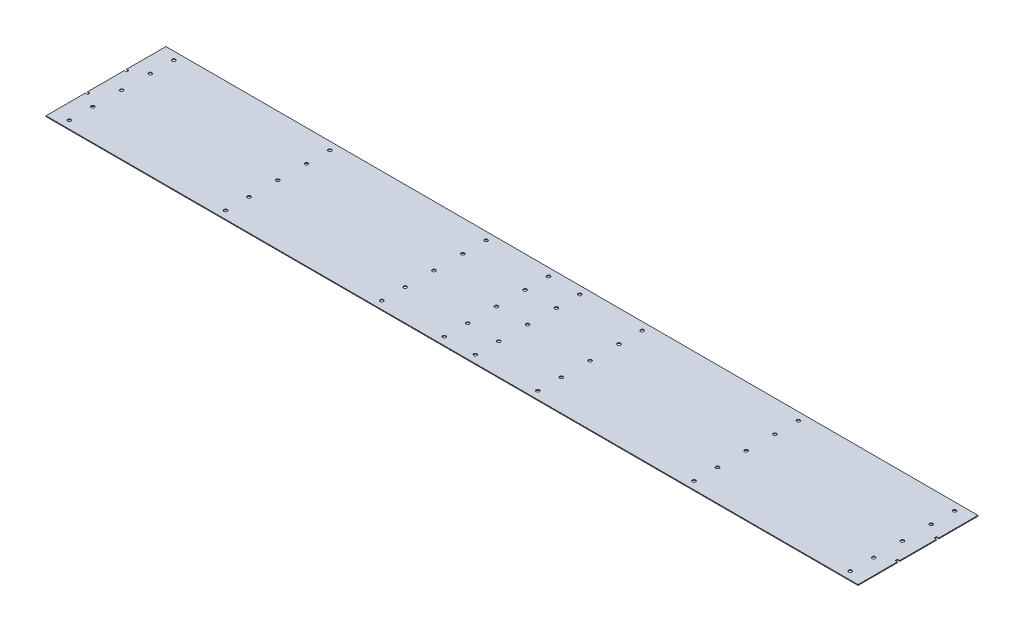
SolidWorks part; units mm, degrees
ref_plane "Front Plane" through (0, 0, 0) normal (0, 0, 1) x (1, 0, 0)
ref_plane "Top Plane" through (0, 0, 0) normal (0, 1, 0) x (1, 0, 0)
ref_plane "Right Plane" through (0, 0, 0) normal (1, 0, 0) x (0, 0, -1)
sketch "Sketch1" plane through (0, 0, 0) normal (0, 1, 0) x (1, 0, 0)
  line L0 (-20, -26.5) -> (-20, -76.8)
  line L1 (-20, -76.8) -> (1020, -76.8)
  line L2 (1020, -76.8) -> (1020, -26.5)
  line L3 (1020, -26.5) -> (-20, -26.5) construction
  line L4 (0, 0) -> (-17, 0) construction
  line L5 (-20, -26.5) -> (-17, -26.5)
  line L7 (-17, 26.5) -> (-20, 26.5)
  line L8 (-20, 26.5) -> (-20, 76.8)
  line L9 (-20, 76.8) -> (1020, 76.8)
  line L10 (1020, 76.8) -> (1020, 26.5)
  line L11 (1020, 26.5) -> (1017, 26.5)
  line L13 (1017, -26.5) -> (1020, -26.5)
  line L14 (0, 36.8) -> (480, 36.8) construction
  line L15 (-17, 26.5) -> (-17, 23.5)
  line L16 (-17, 26.5) -> (1017, 26.5) construction
  line L17 (1017, 26.5) -> (1017, -26.5) construction
  line L18 (-17, 26.5) -> (-17, -26.5) construction
  line L19 (-17, 23.5) -> (-20, 23.5)
  line L20 (-20, 23.5) -> (-20, -23.5)
  line L21 (-20, -23.5) -> (-17, -23.5)
  line L22 (-17, -23.5) -> (-17, -26.5)
  line L23 (1017, 26.5) -> (1017, 23.5)
  line L24 (1017, 23.5) -> (1020, 23.5)
  line L25 (1020, 23.5) -> (1020, -23.5)
  line L26 (1020, -23.5) -> (1017, -23.5)
  line L27 (1017, -23.5) -> (1017, -26.5)
  line L28 (1020, 0) -> (1017, 0) construction
  line L29 (480, 36.8) -> (480, -36.8) construction
  line L30 (-17, 0) -> (-20, 0) construction
  line L31 (0, 36.8) -> (0, -36.8) construction
  line L32 (480, -36.8) -> (0, -36.8) construction
  line L33 (0, 36.8) -> (0, 66.8) construction
  line L34 (0, 66.8) -> (480, 66.8) construction
  line L35 (480, 66.8) -> (480, 36.8) construction
  line L36 (480, -36.8) -> (480, -66.8) construction
  line L37 (480, -66.8) -> (0, -66.8) construction
  line L38 (0, -66.8) -> (0, -36.8) construction
  line L39 (0, 0) -> (480, 0) construction
  line L40 (200, 66.8) -> (200, 36.8) construction
  line L41 (200, 36.8) -> (200, 0) construction
  line L42 (200, 0) -> (200, -36.8) construction
  line L43 (200, -36.8) -> (200, -66.8) construction
  line L44 (500, 76.8) -> (500, -76.8) construction
  line L45 (480, 66.8) -> (500, 66.8) construction
  line L46 (500, 66.8) -> (520, 66.8) construction
  line L47 (520, 66.8) -> (520, -66.8) construction
  line L48 (520, -66.8) -> (480, -66.8) construction
  line L49 (480, -36.8) -> (520, -36.8) construction
  line L50 (400, 66.8) -> (400, -66.8) construction
  line L51 (480, 0) -> (520, 0) construction
  line L53 (480, 36.8) -> (520, 36.8) construction
  line L54 (600, 66.8) -> (600, -66.8) construction
  line L56 (800, 66.8) -> (800, -66.8) construction
  line L58 (1000, 66.8) -> (1000, -66.8) construction
  circle A0 centre (0, -36.8) radius 2.15
  circle A30 centre (0, 36.8) radius 2.15
  circle A31 centre (0, -66.8) radius 2.15
  circle A32 centre (0, 66.8) radius 2.15
  circle A33 centre (200, -66.8) radius 2.15
  circle A34 centre (200, -36.8) radius 2.15
  circle A35 centre (200, 36.8) radius 2.15
  circle A36 centre (200, 66.8) radius 2.15
  circle A53 centre (0, 0) radius 2.15
  circle A54 centre (480, 0) radius 2.15
  circle A55 centre (200, 0) radius 2.15
  circle A59 centre (480, 66.8) radius 2.15
  circle A60 centre (480, 36.8) radius 2.15
  circle A61 centre (480, -36.8) radius 2.15
  circle A62 centre (480, -66.8) radius 2.15
  circle A63 centre (400, -66.8) radius 2.15
  circle A64 centre (400, -36.8) radius 2.15
  circle A65 centre (400, 36.8) radius 2.15
  circle A66 centre (400, 66.8) radius 2.15
  circle A67 centre (600, -66.8) radius 2.15
  circle A68 centre (600, -36.8) radius 2.15
  circle A69 centre (600, 36.8) radius 2.15
  circle A70 centre (600, 66.8) radius 2.15
  circle A71 centre (800, -66.8) radius 2.15
  circle A72 centre (800, -36.8) radius 2.15
  circle A73 centre (800, 36.8) radius 2.15
  circle A74 centre (800, 66.8) radius 2.15
  circle A75 centre (1000, -66.8) radius 2.15
  circle A76 centre (1000, -36.8) radius 2.15
  circle A77 centre (1000, 36.8) radius 2.15
  circle A78 centre (1000, 66.8) radius 2.15
  circle A79 centre (520, -66.8) radius 2.15
  circle A80 centre (520, -36.8) radius 2.15
  circle A81 centre (520, 0) radius 2.15
  circle A82 centre (520, 36.8) radius 2.15
  circle A83 centre (520, 66.8) radius 2.15
  circle A84 centre (600, 0) radius 2.15
  circle A85 centre (800, 0) radius 2.15
  circle A86 centre (1000, 0) radius 2.15
  circle A87 centre (400, 0) radius 2.15
  point P2 (-18.5, 23.5)
  point P17 (0, 51.8)
  dimension "D12" = 4.3
  dimension "D8" = 3
  dimension "D1" = 3
  dimension "D6" = 30
  dimension "D7" = 10
  dimension "D4" = 20
  dimension "D15" = 200
  dimension "D3" = 13.3
  dimension "D11" = 13.3
  dimension "D2" = 47
  dimension "D5" = 20
  dimension "D10" = 40
  dimension "D9" = 6
  dimension "D14" = 2
extrude "Boss-Extrude1" add sketch "Sketch1" along normal blind 1 contours L27 L26 L25 L24 L23 L11 L10 L9 L8 L7 L15 L19 L20 L21 L22 L5 L0 L1 L2 L13 A54 A53 A36 A35 A34 A33 A32 A31 A30 A0
equation "\"skin_sheetmetal_thickness\"= 0.80"
equation "\"base_width_skin_spacer\" = \"base_width_skin_target_width\" - 4 * \"skin_sheetmetal_thickness\" - 2 * \"base_width_skin_target_bend_radius\""
equation "\"base_width_skin_inner\" = \"base_width_skin_spacer\" + 2 * \"skin_sheetmetal_thickness\""
equation "\"base_width_skin_outer\" = \"base_width_skin_inner\" + 2 * \"skin_sheetmetal_thickness\""
equation "\"bend_cut_width\"= 3"
equation "\"bend_cut_length\"= 3"
equation "\"bend_offset_inner\"= 12.5"
equation "\"bend_offset_outer\" = \"bend_offset_inner\" + \"skin_sheetmetal_thickness\""
equation "\"border_offset_ends\"= 20"
equation "\"border_offset_sides\"= 10"
equation "\"border_offset_flange_horiz\"= 10"
equation "\"rivet_size\"= 4.3"
equation "\"rivet_offset_ends\"= \"rivet_spacing_horiz\"/2 - \"border_offset_ends\""
equation "\"rivet_spacing_horiz\"= 200"
equation "\"rivet_spacing_vert\"= 30"
equation "\"rivet_spacing_offset_right\"= 40"
equation "\"base_length\"= 200"
equation "\"base_width_skin_spacer_length\" = 315"
equation "\"bend_offset_spacer_tab\"= 21.0"
equation "\"D6@Sketch1\"=\"rivet_spacing_vert\""
equation "\"D3@Sketch1\"=\"bend_offset_outer\""
equation "\"D1@Sketch1\"=\"bend_cut_length\""
equation "\"D8@Sketch1\"=\"bend_cut_width\""
equation "\"D2@Sketch1\"=\"base_width_skin_outer\""
equation "\"D4@Sketch1\"=\"border_offset_ends\""
equation "\"D7@Sketch1\"=\"border_offset_flange_horiz\""
equation "\"D12@Sketch1\"=\"rivet_size\""
equation "\"D15@Sketch1\"=\"rivet_spacing_horiz\""
equation "\"D5@Sketch1\"=\"border_offset_ends\""
equation "\"D10@Sketch1\"=\"rivet_spacing_offset_right\""
equation "\"base_width_skin_target_width\" = 50"
equation "\"base_width_skin_target_bend_radius\" = 1.5"
